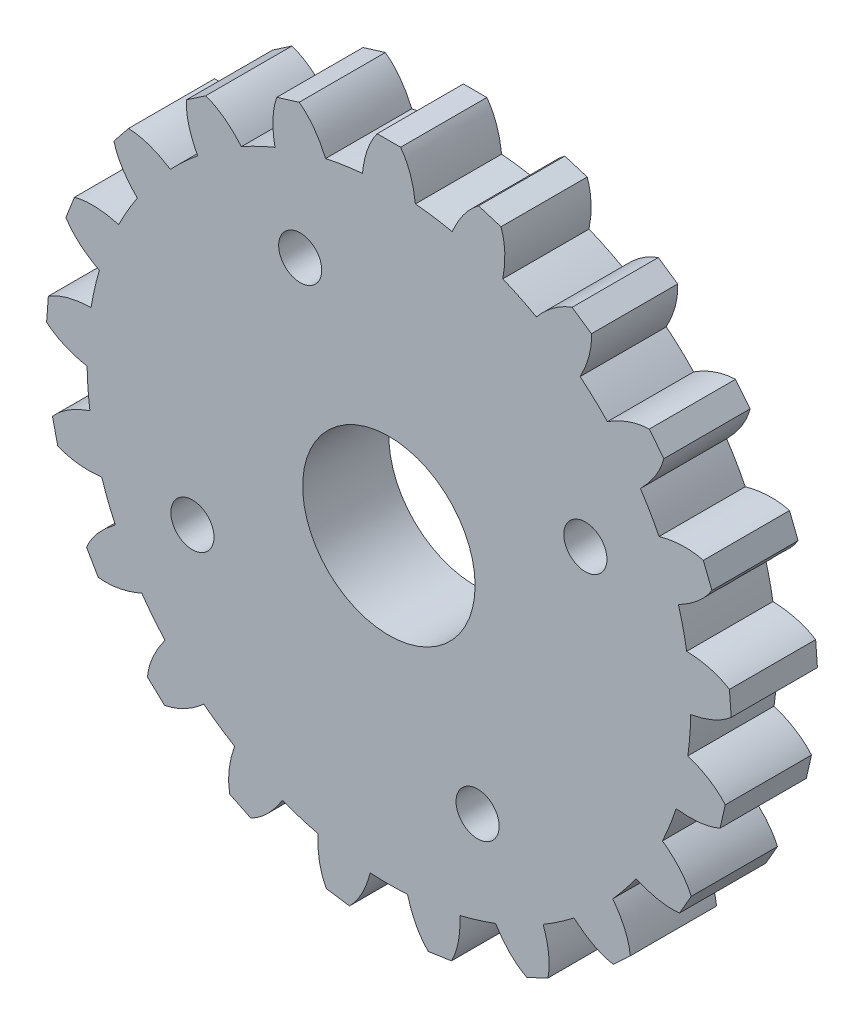
SolidWorks part; units mm, degrees
ref_plane "Vorne" through (0, 0, 0) normal (0, 0, 1) x (1, 0, 0)
ref_plane "Oben" through (0, 0, 0) normal (0, 1, 0) x (1, 0, 0)
ref_plane "Rechts" through (0, 0, 0) normal (1, 0, 0) x (0, 0, -1)
sketch "Skizze1" plane through (0, 0, 0) normal (0, 0, 1) x (1, 0, 0)
  circle A0 centre (0, 0) radius 10.5
  dimension "D1" = 21
extrude "Aufsatz-Linear austragen1" add sketch "Skizze1" along normal blind 3
sketch "Skizze2" plane through (0, 0, 3) normal (0, 0, 1) x (1, 0, 0)
  line L0 (0, 9.1957) -> (0, 14.628) construction
  line L1 (0.921, 10.4595) -> (-0.921, 10.4595)
  line L5 (-0.4077, 11.9118) -> (0.4077, 11.9118)
  circle A1 centre (0, 0) radius 10.5 construction
  spline S0 degree 2 poles (-0.4077, 11.9118) (-0.8249, 11.351) (-0.921, 10.4595) knots 0 0 0 1 1 1
  spline S1 degree 2 poles (0.4077, 11.9118) (0.8249, 11.351) (0.921, 10.4595) knots 0 0 0 1 1 1
  point P11 (0, 10.4595)
  point P12 (0, 11.9118)
extrude "Aufsatz-Linear austragen2" add sketch "Skizze2" against normal blind 3
pattern_circular "Kreismuster1" count 21 over 360 about axis through (0, 0, 3) along (0, 0, 1) of "Aufsatz-Linear austragen2"
sketch "Skizze3" plane through (0, 0, 3) normal (0, 0, 1) x (1, 0, 0)
  circle A0 centre (-3.0857, 6.8358) radius 0.75
  circle A1 centre (6.8358, 3.0857) radius 0.75
  circle A2 centre (-6.8358, -3.0857) radius 0.75
  circle A3 centre (3.0857, -6.8358) radius 0.75
  dimension "D1" = 1.5
  dimension "D2" = 1.5
  dimension "D3" = 1.5
  dimension "D4" = 1.5
extrude "Schnitt-Linear austragen1" cut sketch "Skizze3" against normal blind 6.1
sketch "Skizze4" plane through (0, 0, 3) normal (0, 0, 1) x (1, 0, 0)
  circle A0 centre (0, 0) radius 3
extrude "Schnitt-Linear austragen2" cut sketch "Skizze4" against normal blind 6.1
